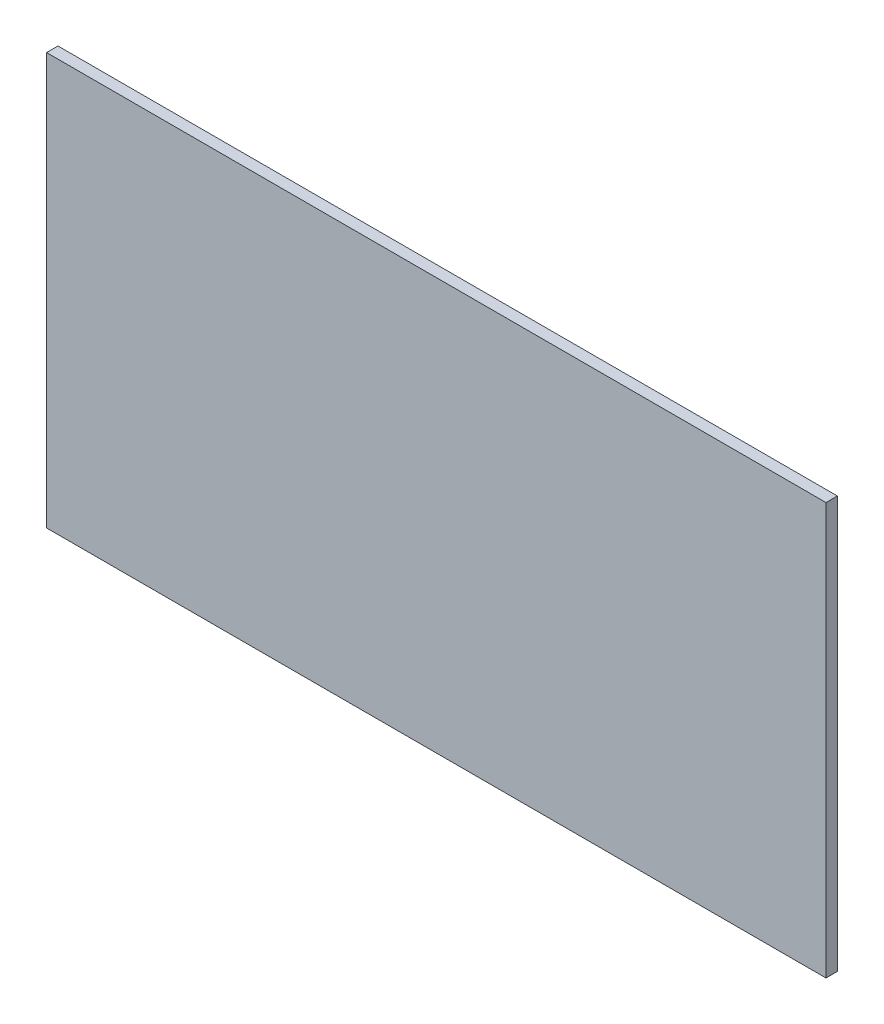
SolidWorks part; units mm, degrees
ref_plane "Plan de face" through (0, 0, 0) normal (0, 0, 1) x (1, 0, 0)
ref_plane "Plan de dessus" through (0, 0, 0) normal (0, 1, 0) x (1, 0, 0)
ref_plane "Plan de droite" through (0, 0, 0) normal (1, 0, 0) x (0, 0, -1)
sketch "Esquisse1" plane through (0, 0, 0) normal (0, 0, 1) x (1, 0, 0)
  line L1 (0, 0) -> (106, 0)
  line L2 (0, 0) -> (0, 56)
  line L3 (0, 56) -> (106, 56)
  line L4 (106, 0) -> (106, 56)
  dimension "D1" = 106
  dimension "D2" = 56
extrude "Boss.-Extru.1" add sketch "Esquisse1" along normal blind 1.55
